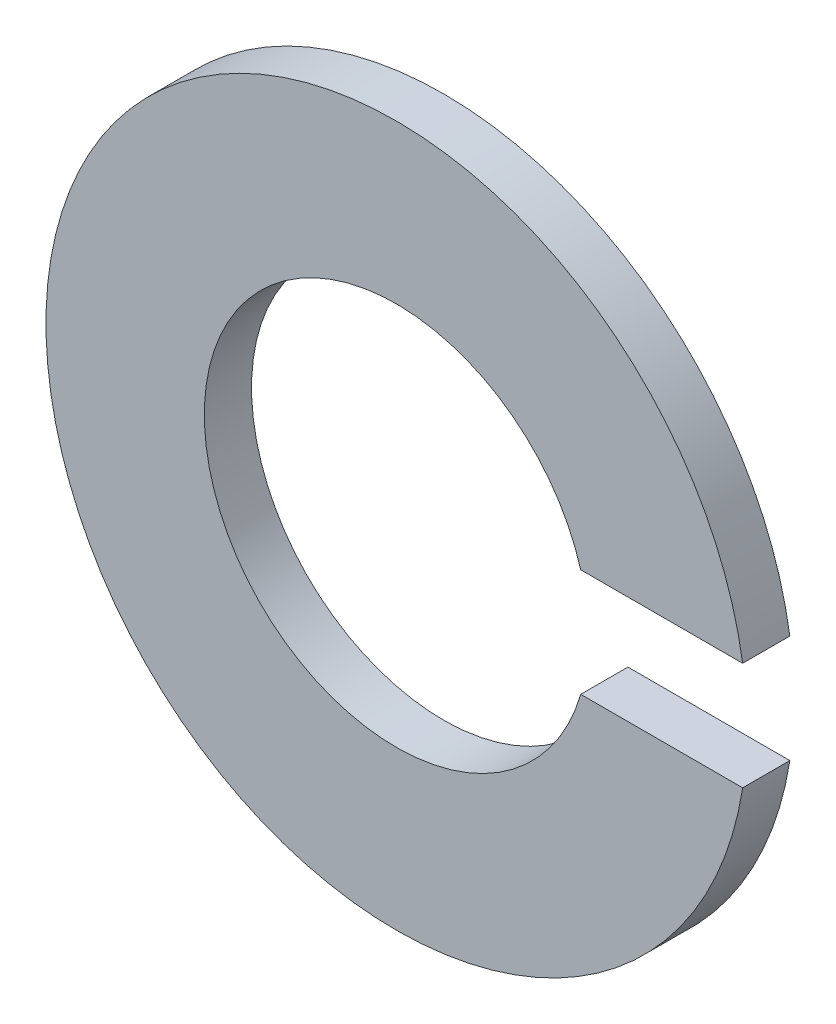
SolidWorks part; units mm, degrees
ref_plane "Front Plane" through (0, 0, 0) normal (0, 0, 1) x (1, 0, 0)
ref_plane "Top Plane" through (0, 0, 0) normal (0, 1, 0) x (1, 0, 0)
ref_plane "Right Plane" through (0, 0, 0) normal (1, 0, 0) x (0, 0, -1)
sketch "Sketch1" plane through (0, 0, 0) normal (0, 0, 1) x (1, 0, 0)
  circle A0 centre (0, 0) radius 5.2
  circle A1 centre (0, 0) radius 2.85
extrude "Installed_Ring_Envelope" add sketch "Sketch1" along normal blind 0.7
sketch "Sketch2" plane through (0, 0, 0.7) normal (0, 0, 1) x (1, 0, 0)
  line L1 (0, -0.8) -> (6, -0.8)
  line L2 (0, -0.8) -> (0, 0.8)
  line L3 (0, 0.8) -> (6, 0.8)
  line L4 (6, -0.8) -> (6, 0.8)
extrude "Split_Opening_Envelope" cut sketch "Sketch2" against normal blind 0.71
